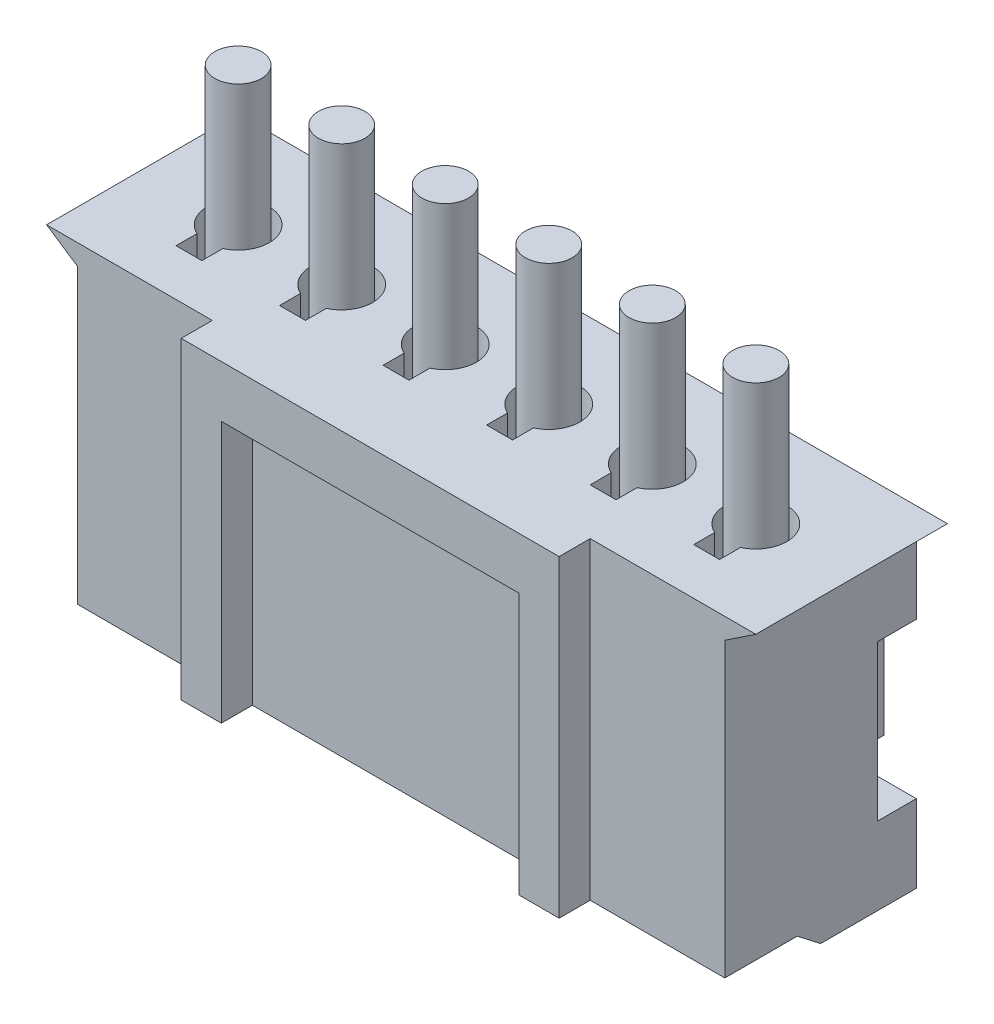
SolidWorks part; units mm, degrees
material "45"
ref_plane "前视基准面" through (0, 0, 0) normal (0, 0, 1) x (1, 0, 0)
ref_plane "上视基准面" through (0, 0, 0) normal (0, 1, 0) x (1, 0, 0)
ref_plane "右视基准面" through (0, 0, 0) normal (1, 0, 0) x (0, 0, -1)
sketch "草图1" plane through (0, 0, 0) normal (0, 1, 0) x (1, 0, 0)
  line L1 (-6.85, 1.85) -> (6.85, 1.85)
  line L2 (-6.85, 1.85) -> (-6.85, -1.85)
  line L3 (-6.85, -1.85) -> (6.85, -1.85)
  line L4 (6.85, 1.85) -> (6.85, -1.85)
  line L5 (-6.85, 1.85) -> (6.85, -1.85) construction
  line L6 (-6.85, -1.85) -> (6.85, 1.85) construction
  point P0 (0, 0)
  dimension "D1" = 13.7
  dimension "D2" = 3.7
extrude "凸台-拉伸1" add sketch "草图1" along normal blind 6.4
sketch "草图2" plane through (0, 0, 1.85) normal (0, 0, 1) x (1, 0, 0)
  line L0 (-6.25, 0) -> (-6.25, 6)
  line L1 (-6.85, 0) -> (6.85, 0) construction
  line L2 (-6.25, 6) -> (-6.85, 6.4)
  line L3 (-6.85, 6.4) -> (-6.85, 0)
  line L4 (-6.85, 0) -> (-6.25, 0)
  line L5 (0, 0) -> (0, 6.4) construction
  line L6 (-6.85, 6.4) -> (6.85, 6.4) construction
  line L7 (6.85, 0) -> (6.25, 0)
  line L8 (6.85, 6.4) -> (6.85, 0)
  line L9 (6.25, 6) -> (6.85, 6.4)
  line L10 (6.25, 0) -> (6.25, 6)
  dimension "D1" = 6.25
  dimension "D2" = 6
extrude "切除-拉伸1" cut sketch "草图2" against normal up to next
sketch "草图4" plane through (0, 0, 1.85) normal (0, 0, 1) x (1, 0, 0)
  line L0 (-6.25, 0) -> (6.25, 0) construction
  line L1 (-3.65, 0) -> (-2.875, 0)
  line L2 (-3.65, 0) -> (-3.65, 6.4)
  line L3 (-3.65, 6.4) -> (3.65, 6.4)
  line L4 (3.65, 0) -> (3.65, 6.4)
  line L5 (-6.85, 6.4) -> (6.85, 6.4) construction
  line L6 (2.875, 0) -> (3.65, 0)
  line L8 (-2.875, 0) -> (-2.875, 5.4)
  line L9 (-2.875, 5.4) -> (2.875, 5.4)
  line L10 (2.875, 0) -> (2.875, 5.4)
  dimension "D1" = 7.3
  dimension "D2" = 1
  dimension "D3" = 5.75
  dimension "D4" = 3.65
  dimension "D5" = 2.875
extrude "凸台-拉伸2" add sketch "草图4" along normal blind 0.6
sketch "草图5" plane through (-6.25, 0, 0) normal (-1, 0, 0) x (0, 0, 1)
  line L0 (2.45, 0.35) -> (0.45, 0.35)
  line L1 (2.45, 6.4) -> (2.45, 0) construction
  line L2 (0.45, 0.35) -> (0, 0)
  line L3 (0, 0) -> (2.45, 0)
  line L4 (2.45, 0) -> (2.45, 0.35)
  dimension "D1" = 0.35
  dimension "D2" = 2
extrude "切除-拉伸2" cut sketch "草图5" against normal up to surface (12.5 mm away) up to face at (6.25, 3, 0)
sketch "草图6" plane through (0, 0.35, 0) normal (0, -1, 0) x (1, 0, 0)
  line L0 (6.25, 0.45) -> (-6.25, 0.45) construction
  line L1 (-5.25, 0.45) -> (-4.75, 0.45)
  line L2 (-5.25, 0.45) -> (-5.25, 0.95)
  line L3 (-5.25, 0.95) -> (-4.75, 0.95)
  line L4 (-4.75, 0.45) -> (-4.75, 0.95)
  dimension "D1" = 0.5
  dimension "D2" = 0.5
  dimension "D3" = 4.75
extrude "切除-拉伸3" cut sketch "草图6" against normal up to surface (6.05 mm away) up to face at (-0.4, 6.4, 1.15)
pattern_linear "阵列(线性)1" count 6 spacing 2 along (1, 0, 0) of "切除-拉伸3"
sketch "草图7" plane through (0, 0, 0) normal (0, -1, 0) x (1, 0, 0)
  line L0 (-4, 0.45) -> (-4, -1.85) construction
  line L1 (-3.25, 0.45) -> (-4.75, 0.45) construction
  line L2 (6.25, -1.85) -> (-6.25, -1.85) construction
  line L4 (-4.25, -1.85) -> (-3.75, -1.85)
  line L5 (-4.25, -1.85) -> (-4.25, -1.35)
  line L6 (-4.25, -1.35) -> (-3.75, -1.35)
  line L7 (-3.75, -1.85) -> (-3.75, -1.35)
  dimension "D1" = 0.5
  dimension "D2" = 0.5
  dimension "D3" = 0.25
extrude "切除-拉伸4" cut sketch "草图7" against normal blind 4.5
pattern_linear "阵列(线性)2" count 5 spacing 2 along (1, 0, 0) of "切除-拉伸4"
sketch "草图8" plane through (0, 0, -1.85) normal (0, 0, -1) x (-1, 0, 0)
  line L0 (-6.25, 0) -> (-6.25, 6) construction
  line L1 (-6.25, 2.25) -> (6.25, 2.25)
  line L2 (-6.25, 2.25) -> (-6.25, 1.5)
  line L3 (-6.25, 1.5) -> (6.25, 1.5)
  line L4 (6.25, 2.25) -> (6.25, 1.5)
  line L5 (6.25, 6) -> (6.25, 0) construction
  line L6 (-6.25, 0) -> (-4.25, 0) construction
  dimension "D1" = 1.5
  dimension "D2" = 0.75
extrude "切除-拉伸5" cut sketch "草图8" against normal blind 0.75
sketch "草图9" plane through (0, 0, -1.85) normal (0, 0, -1) x (-1, 0, 0)
  line L0 (-6.25, 0) -> (-6.25, 1.5) construction
  line L1 (-6.375, 1.5) -> (-5.625, 1.5)
  line L2 (-6.375, 1.5) -> (-6.375, 4.5)
  line L3 (-6.375, 4.5) -> (-5.625, 4.5)
  line L4 (-5.625, 1.5) -> (-5.625, 4.5)
  dimension "D1" = 0.75
  dimension "D2" = 3
  dimension "D3" = 0.125
extrude "切除-拉伸6" cut sketch "草图9" against normal blind 0.75
pattern_linear "阵列(线性)3" count 7 spacing 2 along (-1, 0, 0) of "切除-拉伸6"
sketch "草图10" plane through (0, 0, -1.85) normal (0, 0, -1) x (-1, 0, 0)
  line L0 (-5, 2.25) -> (-5, 0.5073) construction
  line L1 (-4.375, 2.25) -> (-5.625, 2.25) construction
  line L3 (-5.375, 1.8647) -> (-4.625, 1.8647)
  line L4 (-5.375, 1.8647) -> (-5.375, 0.6)
  line L5 (-5.375, 0.6) -> (-4.625, 0.6)
  line L6 (-4.625, 1.8647) -> (-4.625, 0.6)
  line L7 (-5.375, 1.8647) -> (-4.625, 0.6) construction
  line L8 (-5.375, 0.6) -> (-4.625, 1.8647) construction
  line L9 (-6.25, 0) -> (-4.25, 0) construction
  point P11 (-5.25, 0)
  dimension "D1" = 0.6
  dimension "D2" = 0.75
  dimension "D3" = 0.375
extrude "切除-拉伸7" cut sketch "草图10" against normal blind 2.5
pattern_linear "阵列(线性)4" count 6 spacing 2 along (-1, 0, 0) of "切除-拉伸7"
sketch "草图11" plane through (0, 6.4, 0) normal (0, 1, 0) x (1, 0, 0)
  line L0 (-5, -0.45) -> (-5, 0.6551) construction
  line L3 (-5.25, -0.45) -> (-4.75, -0.45) construction
  circle A0 centre (-5, 0) radius 0.6
  dimension "D1" = 1.2
extrude "切除-拉伸8" cut sketch "草图11" against normal blind 2.5
pattern_linear "阵列(线性)5" count 6 spacing 2 along (1, 0, 0) of "切除-拉伸8"
sketch "草图12" plane through (0, 3.9, 0) normal (0, 1, 0) x (1, 0, 0)
  circle A0 centre (-5, 0) radius 0.45
  dimension "D1" = 0.9
extrude "凸台-拉伸4" add sketch "草图12" along normal blind 3
pattern_linear "阵列(线性)6" count 6 spacing 2 along (1, 0, 0) of "凸台-拉伸4"
ref_plane "基准面1" through (-5, 0, 0) normal (-1, 0, 0) x (0, 0, 1)
sketch "草图13" plane through (-5, 0, 0) normal (-1, 0, 0) x (0, 0, 1)
  line L0 (0.45, 6.9) -> (-0.45, 6.9) construction
  line L1 (0, 6.9) -> (0, 7.3275) construction
  line L2 (0, 6.9) -> (0, 13.0728)
sketch "草图15" plane through (0, 6.9, 0) normal (0, 1, 0) x (1, 0, 0)
  circle A0 centre (-5, 0) radius 0.45
  dimension "D1" = 0.9
sweep "扫描1" add profiles "草图15" path "草图13"
pattern_linear "阵列(线性)7" count 6 spacing 2 along (1, 0, 0) of "扫描1"
sketch "草图16" plane through (0, 13.0728, 0) normal (0, 1, 0) x (1, 0, 0)
  line L1 (-10.5413, 3.9713) -> (8.4789, 3.9713)
  line L2 (-10.5413, 3.9713) -> (-10.5413, -3.0922)
  line L3 (-10.5413, -3.0922) -> (8.4789, -3.0922)
  line L4 (8.4789, 3.9713) -> (8.4789, -3.0922)
extrude "切除-拉伸9" cut sketch "草图16" against normal blind 4
